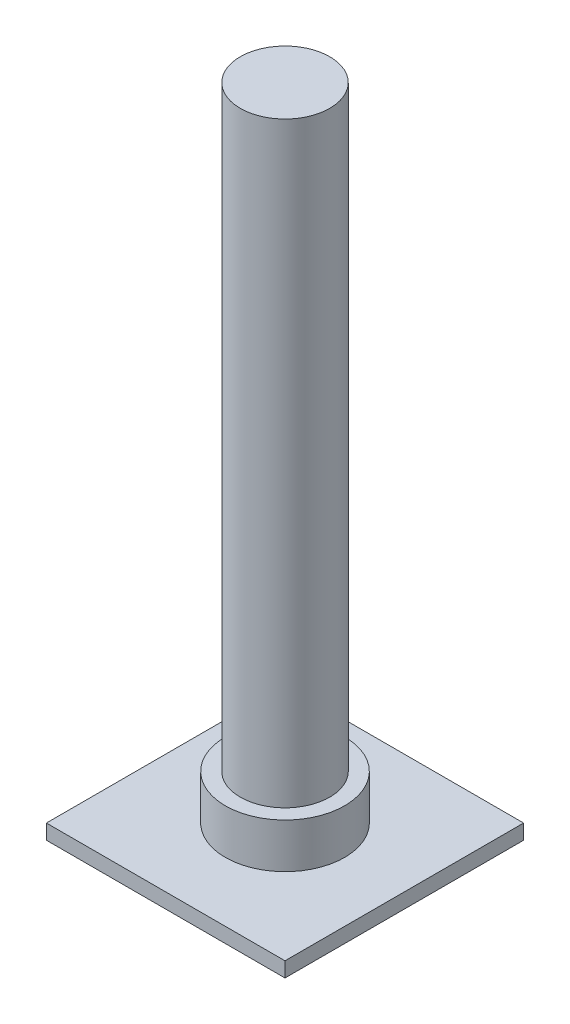
SolidWorks part; units mm, degrees
material "自定义塑料"
ref_plane "前视基准面" through (0, 0, 0) normal (0, 0, 1) x (1, 0, 0)
ref_plane "上视基准面" through (0, 0, 0) normal (0, 1, 0) x (1, 0, 0)
ref_plane "右视基准面" through (0, 0, 0) normal (1, 0, 0) x (0, 0, -1)
sketch "草图1" plane through (0, 0, 0) normal (0, 1, 0) x (1, 0, 0)
  line L1 (0, 0) -> (80, 0)
  line L2 (0, 0) -> (0, 80)
  line L3 (0, 80) -> (80, 80)
  line L4 (80, 0) -> (80, 80)
extrude "凸台-拉伸1" add sketch "草图1" along normal blind 5
sketch "草图2" plane through (0, 5, 0) normal (0, 1, 0) x (1, 0, 0)
  circle A0 centre (40, 40) radius 20
extrude "凸台-拉伸2" add sketch "草图2" along normal blind 15
sketch "草图3" plane through (0, 20, 0) normal (0, 1, 0) x (1, 0, 0)
  circle A0 centre (40, 40) radius 15
extrude "凸台-拉伸3" add sketch "草图3" along normal blind 200
